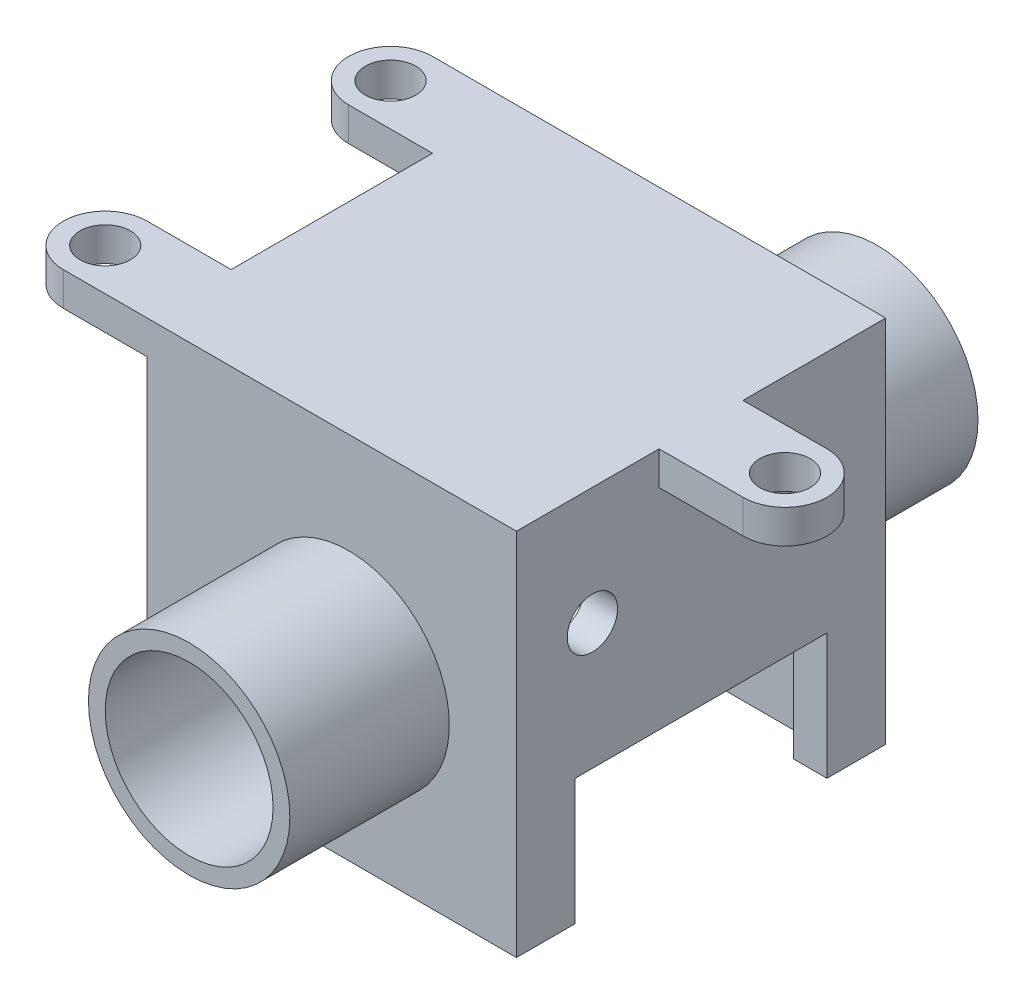
SolidWorks part; units mm, degrees
ref_plane "Front Plane" through (0, 0, 0) normal (0, 0, 1) x (1, 0, 0)
ref_plane "Top Plane" through (0, 0, 0) normal (0, 1, 0) x (1, 0, 0)
ref_plane "Right Plane" through (0, 0, 0) normal (1, 0, 0) x (0, 0, -1)
sketch "Sketch1" plane through (0, 0, 0) normal (0, 1, 0) x (1, 0, 0)
  line L1 (-11, 11) -> (11, 11)
  line L2 (-11, 11) -> (-11, -11)
  line L3 (-11, -11) -> (11, -11)
  line L4 (11, 11) -> (11, -11)
  line L5 (-11, 11) -> (11, -11) construction
  line L6 (-11, -11) -> (11, 11) construction
  point P0 (0, 0)
  dimension "D1" = 22
extrude "Boss-Extrude1" add sketch "Sketch1" along normal mid plane 20
shell "Shell1" thickness 2
sketch "Sketch2" plane through (11, 0, 0) normal (1, 0, 0) x (0, 0, -1)
  line L0 (0, 6.1845) -> (0, -4.7754) construction
  line L1 (-7.5, -10) -> (-7.5, -2.5)
  line L2 (-11, -10) -> (11, -10) construction
  line L3 (-7.5, -2.5) -> (7.5, -2.5)
  line L4 (7.5, -10) -> (7.5, -2.5)
  line L5 (-7.5, -10) -> (7.5, -10)
  circle A0 centre (-6.475, 5) radius 1.5
  circle A1 centre (6.475, 5) radius 1.5
  point P10 (0, -2.5)
  dimension "D3" = 3
  dimension "D1" = 7.5
  dimension "D2" = 7.5
  dimension "D4" = 12.95
  dimension "D5" = 15
extrude "Cut-Extrude1" cut sketch "Sketch2" against normal blind 8
sketch "Sketch3" plane through (-11, 0, 0) normal (-1, 0, 0) x (0, 0, 1)
  line L0 (-11, 10) -> (11, 10) construction
  circle A0 centre (0, 0) radius 2.55
  dimension "D1" = 5.1
  dimension "D2" = 10
extrude "Cut-Extrude2" cut sketch "Sketch3" against normal blind 8
sketch "Sketch4" plane through (0, 0, -11) normal (0, 0, -1) x (-1, 0, 0)
  circle A0 centre (-1, 0) radius 5
  dimension "D1" = 10
  dimension "D2" = 1
extrude "Cut-Extrude3" cut sketch "Sketch4" against normal through all both and the other way through all
sketch "Sketch5" plane through (0, 0, 0) normal (0, 0, 1) x (1, 0, 0)
  circle A0 centre (1, 0) radius 6
  circle A1 centre (1, 0) radius 5
  point P4 (0, 0)
  point P5 (2, 0)
  point P6 (0, 0)
  point P7 (2, 0)
  dimension "D1" = 12
  dimension "D2" = 10
extrude "Boss-Extrude2" add sketch "Sketch5" along normal blind 10 from offset 10.5
mirror "Mirror4" about plane through (0, 0, 0) normal (0, 0, 1) of "Boss-Extrude2"
sketch "Sketch7" plane through (0, 10, 0) normal (0, 1, 0) x (1, 0, 0)
  line L0 (-18.3486, -8.5) -> (22.5747, -8.5) construction
  line L1 (-11, -6) -> (-16, -6)
  line L2 (-11, 11) -> (-11, -11) construction
  line L3 (-11, -11) -> (-16, -11)
  line L4 (-11, -8.5) -> (-11, -11) construction
  line L5 (0, 4.983) -> (0, -2.5) construction
  line L9 (-15.1581, 0) -> (15.0868, 0) construction
  line L10 (-11, 6) -> (-16, 6)
  line L11 (-11, 11) -> (-16, 11)
  line L12 (-11, 6) -> (-11, 11) construction
  line L16 (11, 2.5) -> (16, 2.5)
  line L17 (11, -11) -> (11, 11) construction
  line L18 (11, -2.5) -> (16, -2.5)
  line L19 (11, -2.5) -> (11, 0) construction
  line L20 (-11, 11) -> (11, 11)
  line L21 (11, 11) -> (11, 2.5)
  line L22 (11, -2.5) -> (11, -11)
  line L23 (11, -11) -> (-11, -11)
  line L24 (-11, 6) -> (-11, -6)
  line L25 (11, 0) -> (11, 2.5) construction
  line L26 (-11, -6) -> (-11, -8.5) construction
  arc A0 (-16, -6) -> (-16, -11) centre (-16, -8.5) ccw
  circle A1 centre (-16, -8.5) radius 1.5
  circle A4 centre (-16, 8.5) radius 1.5
  arc A5 (-16, 6) -> (-16, 11) centre (-16, 8.5) cw
  arc A8 (16, 2.5) -> (16, -2.5) centre (16, 0) cw
  circle A9 centre (16, 0) radius 1.5
  dimension "D1" = 2.5
  dimension "D2" = 3
  dimension "D3" = 3
  dimension "D4" = 2.5
  dimension "D6" = 2.5
  dimension "D8" = 3
  dimension "D5" = 5
  dimension "D7" = 5
extrude "Boss-Extrude3" add sketch "Sketch7" along normal blind 2
